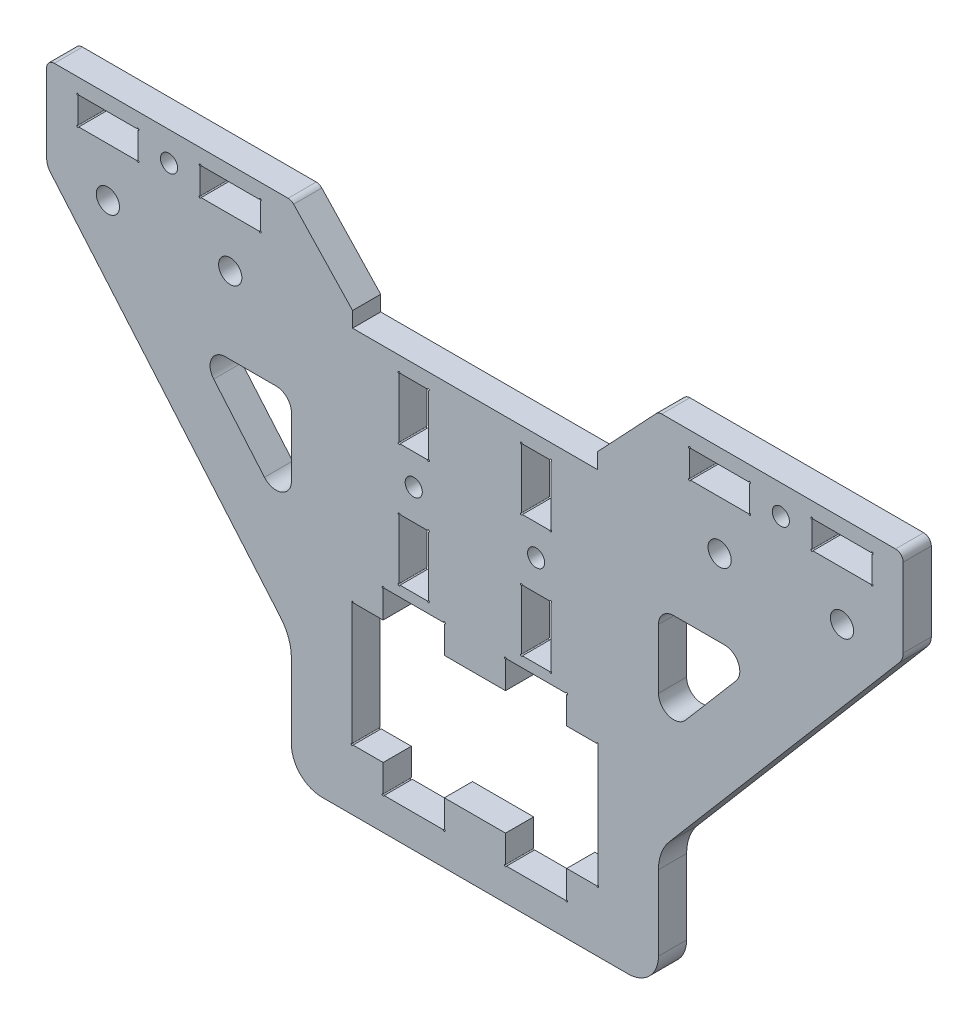
SolidWorks part; units mm, degrees
ref_plane "Front Plane" through (0, 0, 0) normal (0, 0, 1) x (1, 0, 0)
ref_plane "Top Plane" through (0, 0, 0) normal (0, 1, 0) x (1, 0, 0)
ref_plane "Right Plane" through (0, 0, 0) normal (1, 0, 0) x (0, 0, -1)
sketch "Sketch1" plane through (0, 0, 0) normal (0, 0, 1) x (1, 0, 0)
  line L0 (0, 0) -> (-101.6, 0) construction
  line L1 (-25.4, 2.4354) -> (-76.2, 2.4354)
  line L2 (0, 0) -> (12.7, 0) construction
  line L3 (12.7, 0) -> (12.7, 41.9354) construction
  line L4 (12.7, 0) -> (25.4, 0) construction
  line L5 (-101.6, 0) -> (-114.3, 0) construction
  line L6 (-114.3, 0) -> (-127, 0) construction
  line L7 (-114.3, 0) -> (-114.3, 41.9354) construction
  line L8 (49.2125, 41.9354) -> (-23.8125, 41.9354) construction
  line L9 (-150.8125, 41.9354) -> (-77.7875, 41.9354) construction
  line L10 (6.25, 10.1854) -> (-6.25, 10.1854)
  line L11 (19.15, 15.9274) -> (31.65, 15.9274)
  line L12 (19.15, 15.9274) -> (19.15, 10.1854)
  line L13 (33.7058, 10.1854) -> (-8.3058, 10.1854) construction
  line L14 (33.7058, 10.1854) -> (33.7058, 15.9274) construction
  line L15 (33.7058, 15.9274) -> (-8.3058, 15.9274) construction
  line L16 (-8.3058, 10.1854) -> (-8.3058, 15.9274) construction
  line L17 (12.7, 15.9274) -> (12.7, 10.1854) construction
  line L18 (33.7058, 13.0564) -> (-8.3058, 13.0564) construction
  line L19 (19.15, 10.1854) -> (31.65, 10.1854)
  line L20 (31.65, 15.9274) -> (31.65, 10.1854)
  line L21 (19.15, 15.9274) -> (31.65, 10.1854) construction
  line L22 (19.15, 10.1854) -> (31.65, 15.9274) construction
  line L23 (-6.25, 15.9274) -> (-6.25, 10.1854)
  line L24 (6.25, 15.9274) -> (-6.25, 15.9274)
  line L25 (6.25, 15.9274) -> (6.25, 10.1854)
  line L26 (38.1, 19.1024) -> (-12.7, 19.1024)
  line L27 (-25.4, 2.4354) -> (-25.4, 5.6104)
  line L28 (-50.8, 41.9354) -> (-50.8, -59.6646) construction
  line L29 (38.1, 19.1024) -> (38.1, 0)
  line L30 (-25.4, -72.3646) -> (-76.2, -72.3646) construction
  line L31 (-25.4, -72.3646) -> (-25.4, -46.9646) construction
  line L32 (-25.4, -46.9646) -> (-76.2, -46.9646) construction
  line L33 (-76.2, -72.3646) -> (-76.2, -46.9646) construction
  line L34 (-25.4, -72.3646) -> (-76.2, -46.9646) construction
  line L35 (-25.4, -46.9646) -> (-76.2, -72.3646) construction
  line L36 (-25.4, 5.6104) -> (-12.7, 19.1024)
  line L37 (-25.3, -72.4646) -> (-76.3, -72.4646)
  line L38 (-25.3, -72.4646) -> (-25.3, -46.8646)
  line L39 (-25.3, -46.8646) -> (-76.3, -46.8646)
  line L40 (-76.3, -72.4646) -> (-76.3, -46.8646)
  line L41 (-25.3, -72.4646) -> (-76.3, -46.8646) construction
  line L42 (-25.3, -46.8646) -> (-76.3, -72.4646) construction
  line L43 (-12.7, -59.6646) -> (38.1, 0)
  line L44 (-12.7, -85.0646) -> (-88.9, -85.0646)
  line L45 (-12.7, -85.0646) -> (-12.7, -59.6646)
  line L47 (-12.7, -40.0743) -> (7.8828, -15.8997)
  line L48 (-12.7, -85.0646) -> (-88.9, -34.2646) construction
  line L49 (-12.7, -34.2646) -> (-88.9, -85.0646) construction
  line L56 (-12.7, -59.6646) -> (-12.7, -40.0743) construction
  line L57 (-12.7, -40.0743) -> (-12.7, -15.8997)
  line L58 (-12.7, -15.8997) -> (7.8828, -15.8997)
  line L67 (-88.9, -59.6646) -> (-88.9, -40.0743) construction
  line L70 (-88.9, -34.2646) -> (-12.7, -85.0646) construction
  line L71 (-120.75, 10.1854) -> (-133.25, 15.9274) construction
  line L72 (-120.75, 15.9274) -> (-133.25, 10.1854) construction
  line L73 (-135.3058, 13.0564) -> (-93.2942, 13.0564) construction
  line L74 (-114.3, 15.9274) -> (-114.3, 10.1854) construction
  line L75 (-93.2942, 10.1854) -> (-93.2942, 15.9274) construction
  line L76 (-135.3058, 15.9274) -> (-93.2942, 15.9274) construction
  line L77 (-135.3058, 10.1854) -> (-135.3058, 15.9274) construction
  line L78 (-135.3058, 10.1854) -> (-93.2942, 10.1854) construction
  line L79 (-114.3, 0) -> (-127, 0) construction
  line L80 (-114.3, 0) -> (-114.3, 41.9354) construction
  line L81 (-101.6, 0) -> (-114.3, 0) construction
  line L86 (-88.9, -15.8997) -> (-109.4828, -15.8997)
  line L87 (-88.9, -40.0743) -> (-88.9, -15.8997)
  line L92 (-88.9, -40.0743) -> (-109.4828, -15.8997)
  line L93 (-88.9, -59.6646) -> (-139.7, 0)
  line L94 (-76.2, 5.6104) -> (-88.9, 19.1024)
  line L95 (-139.7, 19.1024) -> (-139.7, 0)
  line L96 (-76.2, 2.4354) -> (-76.2, 5.6104)
  line L97 (-139.7, 19.1024) -> (-88.9, 19.1024)
  line L98 (-107.85, 15.9274) -> (-107.85, 10.1854)
  line L99 (-107.85, 15.9274) -> (-95.35, 15.9274)
  line L100 (-95.35, 15.9274) -> (-95.35, 10.1854)
  line L101 (-133.25, 15.9274) -> (-133.25, 10.1854)
  line L102 (-120.75, 10.1854) -> (-133.25, 10.1854)
  line L103 (-120.75, 15.9274) -> (-120.75, 10.1854)
  line L104 (-120.75, 15.9274) -> (-133.25, 15.9274)
  line L105 (-107.85, 10.1854) -> (-95.35, 10.1854)
  line L106 (-88.9, -85.0646) -> (-88.9, -59.6646)
  circle A0 centre (0, 0) radius 2.413
  circle A1 centre (-101.6, 0) radius 2.413
  circle A2 centre (25.4, 0) radius 2.413
  circle A3 centre (-127, 0) radius 2.413
  circle A4 centre (-50.8, 41.9354) radius 34.925 construction
  circle A5 centre (12.7, 13.0564) radius 1.778
  circle A24 centre (-114.3, 13.0564) radius 1.778
  circle A25 centre (-127, 0) radius 2.413
  circle A26 centre (-101.6, 0) radius 2.413
  ellipse E0 centre (-50.8, 41.9354) end of major axis (-50.8, 76.8604) minor radius 26.9875 construction
  point P5 (-114.3, 19.1024)
  point P17 (12.7, 41.9354)
  point P22 (12.7, 13.0564)
  point P25 (12.7, 13.1064)
  point P28 (12.7, 10.1854)
  point P32 (25.4, 13.0564)
  point P42 (12.7, 19.1024)
  point P48 (-50.8, 0.4064)
  point P51 (-50.8, -59.6646)
  point P68 (-50.8, -10.7061)
  point P100 (-50.8, -20.2311)
  point P126 (-50.8, -22.225)
  point P163 (-50.8, 2.4354)
  point P164 (-127, 13.0564)
  point P165 (-114.3, 13.1064)
  dimension "D1" = 4.826
  dimension "D2" = 4.826
  dimension "D4" = 4.826
  dimension "D5" = 4.826
  dimension "D9" = 69.85
  dimension "D16" = 3.556
  dimension "D3" = 12.7
  dimension "D6" = 12.7
  dimension "D7" = 127
  dimension "D8" = 73.025
  dimension "D10" = 31.75
  dimension "D11" = 10.1854
  dimension "D12" = 12.5
  dimension "D13" = 5.742
  dimension "D14" = 42.0116
  dimension "D15" = 12.7
  dimension "D17" = 50.8
  dimension "D18" = 4.575
  dimension "D19" = 3.175
  dimension "D20" = 101.6
  dimension "D21" = 50.8
  dimension "D22" = 25.4
  dimension "D23" = 25.4
  dimension "D24" = 51
  dimension "D25" = 25.6
  dimension "D26" = 3.175
  dimension "D28" = 50.8
  dimension "D29" = 25.4
  dimension "D37" = 12.7
  dimension "D38" = 31.75
extrude "Boss-Extrude1" add sketch "Sketch1" along normal blind 5.842
fillet "Fillet1" radius 6.35 2 edges at (-12.7, -85.0646, 2.921) (-88.9, -85.0646, 2.921)
fillet "Fillet2" radius 3.175 6 edges at (7.8828, -15.8997, 2.921) (-12.7, -40.0743, 2.921) (-12.7, -15.8997, 2.921) (-88.9, -15.8997, 2.921) (-88.9, -40.0743, 2.921) (-109.4828, -15.8997, 2.921)
fillet "Fillet3" radius 3.175 2 edges at (-139.7, 0, 2.921) (38.1, 0, 2.921)
fillet "Fillet4" radius 1.5875 4 edges at (38.1, 19.1024, 2.921) (-12.7, 19.1024, 2.921) (-88.9, 19.1024, 2.921) (-139.7, 19.1024, 2.921)
fillet "Fillet5" radius 9.525 2 edges at (-88.9, -59.6646, 2.921) (-12.7, -59.6646, 2.921)
sketch "Sketch2" plane through (0, 0, 5.842) normal (0, 0, 1) x (1, 0, 0)
  line L0 (-50.8, 2.4354) -> (-50.8, -46.8646) construction
  line L1 (-25.4, 2.4354) -> (-76.2, 2.4354) construction
  line L2 (-25.3, -46.8646) -> (-76.3, -46.8646) construction
  line L3 (-38.1, -19.7896) -> (-63.5, -19.7896) construction
  line L4 (-38.1, -32.4896) -> (-38.1, -7.0896) construction
  line L5 (-35.052, -26.1396) -> (-41.148, -38.8396) construction
  line L6 (-35.052, -0.7396) -> (-41.148, -0.7396)
  line L7 (-35.052, -0.7396) -> (-35.052, -13.4396)
  line L8 (-35.052, -13.4396) -> (-41.148, -13.4396)
  line L9 (-41.148, -0.7396) -> (-41.148, -13.4396)
  line L10 (-35.052, -0.7396) -> (-41.148, -13.4396) construction
  line L11 (-35.052, -13.4396) -> (-41.148, -0.7396) construction
  line L12 (-35.052, -38.8396) -> (-41.148, -26.1396) construction
  line L13 (-41.148, -38.8396) -> (-41.148, -26.1396)
  line L14 (-35.052, -26.1396) -> (-41.148, -26.1396)
  line L15 (-35.052, -38.8396) -> (-35.052, -26.1396)
  line L16 (-35.052, -38.8396) -> (-41.148, -38.8396)
  line L17 (-66.548, -38.8396) -> (-60.452, -26.1396) construction
  line L18 (-66.548, -13.4396) -> (-60.452, -0.7396) construction
  line L19 (-66.548, -0.7396) -> (-60.452, -13.4396) construction
  line L20 (-66.548, -26.1396) -> (-60.452, -38.8396) construction
  line L21 (-63.5, -32.4896) -> (-63.5, -7.0896) construction
  line L22 (-66.548, -38.8396) -> (-60.452, -38.8396)
  line L23 (-66.548, -38.8396) -> (-66.548, -26.1396)
  line L24 (-66.548, -26.1396) -> (-60.452, -26.1396)
  line L25 (-60.452, -38.8396) -> (-60.452, -26.1396)
  line L26 (-60.452, -0.7396) -> (-60.452, -13.4396)
  line L27 (-66.548, -13.4396) -> (-60.452, -13.4396)
  line L28 (-66.548, -0.7396) -> (-66.548, -13.4396)
  line L29 (-66.548, -0.7396) -> (-60.452, -0.7396)
  circle A0 centre (-38.1, -19.7896) radius 1.778
  circle A1 centre (-63.5, -19.7896) radius 1.778
  point P9 (-50.8, -19.7896)
  point P12 (-38.1, -19.7896)
  dimension "D6" = 3.556
  dimension "D1" = 25.4
  dimension "D2" = 25.4
  dimension "D3" = 22.225
  dimension "D4" = 6.096
  dimension "D5" = 12.7
extrude "Cut-Extrude1" cut sketch "Sketch2" against normal through all
sketch "Sketch3" plane through (0, 0, 5.842) normal (0, 0, 1) x (1, 0, 0)
  line L1 (-50.8, 2.4354) -> (-50.8, -46.8646) construction
  line L2 (-25.4, 2.4354) -> (-76.2, 2.4354) construction
  line L3 (-25.3, -46.8646) -> (-76.3, -46.8646) construction
  circle A0 centre (-35.052, -26.1396) radius 0.1984
  circle A1 centre (-41.148, -26.1396) radius 0.1984
  circle A2 centre (-35.052, -38.8396) radius 0.1984
  circle A3 centre (-41.148, -38.8396) radius 0.1984
  circle A4 centre (-35.052, -0.7396) radius 0.1984
  circle A5 centre (-35.052, -13.4396) radius 0.1984
  circle A6 centre (-41.148, -13.4396) radius 0.1984
  circle A7 centre (-41.148, -0.7396) radius 0.1984
  circle A24 centre (-60.452, -0.7396) radius 0.1984
  circle A25 centre (-60.452, -13.4396) radius 0.1984
  circle A26 centre (-66.548, -13.4396) radius 0.1984
  circle A27 centre (-66.548, -0.7396) radius 0.1984
  circle A28 centre (-60.452, -38.8396) radius 0.1984
  circle A29 centre (-66.548, -38.8396) radius 0.1984
  circle A30 centre (-60.452, -26.1396) radius 0.1984
  circle A31 centre (-66.548, -26.1396) radius 0.1984
  dimension "D9" = 0.3969
  dimension "D10" = 0.3969
  dimension "D11" = 0.3969
  dimension "D12" = 0.3969
  dimension "D13" = 0.3969
  dimension "D14" = 0.3969
  dimension "D15" = 0.3969
  dimension "D16" = 0.3969
extrude "Cut-Extrude2" cut sketch "Sketch3" against normal through all
sketch "Sketch5" plane through (0, 0, 5.842) normal (0, 0, 1) x (1, 0, 0)
  line L0 (19.15, 15.9274) -> (19.15, 10.1854) construction
  line L1 (19.15, 15.9274) -> (31.65, 15.9274) construction
  line L2 (-50.8, 2.4354) -> (-50.8, -46.8646) construction
  line L3 (-25.4, 2.4354) -> (-76.2, 2.4354) construction
  line L4 (-25.3, -46.8646) -> (-76.3, -46.8646) construction
  circle A0 centre (31.65, 15.9274) radius 0.1984
  circle A1 centre (31.65, 10.1854) radius 0.1984
  circle A2 centre (19.15, 10.1854) radius 0.1984
  circle A3 centre (19.15, 15.9274) radius 0.1984
  circle A4 centre (6.25, 15.9274) radius 0.1984
  circle A5 centre (6.25, 10.1854) radius 0.1984
  circle A6 centre (-6.25, 15.9274) radius 0.1984
  circle A7 centre (-6.25, 10.1854) radius 0.1984
  circle A8 centre (-95.35, 10.1854) radius 0.1984
  circle A9 centre (-95.35, 15.9274) radius 0.1984
  circle A10 centre (-107.85, 10.1854) radius 0.1984
  circle A11 centre (-107.85, 15.9274) radius 0.1984
  circle A12 centre (-120.75, 15.9274) radius 0.1984
  circle A13 centre (-120.75, 10.1854) radius 0.1984
  circle A14 centre (-133.25, 10.1854) radius 0.1984
  circle A15 centre (-133.25, 15.9274) radius 0.1984
  circle A16 centre (-25.3, -46.8646) radius 0.1984
  circle A17 centre (-25.3, -72.4646) radius 0.1984
  circle A18 centre (-76.3, -72.4646) radius 0.1984
  circle A19 centre (-76.3, -46.8646) radius 0.1984
  dimension "D1" = 0.3969
  dimension "D2" = 0.3969
  dimension "D3" = 0.3969
  dimension "D4" = 0.3969
  dimension "D5" = 0.3969
  dimension "D6" = 0.3969
  dimension "D7" = 0.3969
  dimension "D8" = 0.3969
  dimension "D9" = 0.3969
  dimension "D10" = 0.3969
  dimension "D11" = 0.3969
  dimension "D12" = 0.3969
extrude "Cut-Extrude3" cut sketch "Sketch5" against normal through all
sketch "Sketch6" [suppressed] plane through (0, 0, 5.842) normal (0, 0, 1) x (1, 0, 0)
  line L0 (-76.3, -72.2662) -> (-76.3, -47.063) construction
  line L1 (-76.3, -59.6646) -> (-25.3, -59.6646) construction
  line L2 (-25.3, -72.2662) -> (-25.3, -47.063) construction
  line L3 (-82.142, -43.7896) -> (-76.3, -43.7896)
  line L4 (-82.142, -43.7896) -> (-82.142, -56.4896)
  line L5 (-82.142, -56.4896) -> (-76.3, -56.4896)
  line L6 (-76.3, -43.7896) -> (-76.3, -56.4896)
  line L7 (-82.142, -43.7896) -> (-76.3, -56.4896) construction
  line L8 (-82.142, -56.4896) -> (-76.3, -43.7896) construction
  line L9 (-79.221, -50.1396) -> (-79.221, -75.5396) construction
  line L10 (-44.45, -46.8646) -> (-31.75, -41.0226) construction
  line L11 (-44.45, -41.0226) -> (-31.75, -46.8646) construction
  line L12 (-76.3, -62.8396) -> (-82.142, -62.8396) construction
  line L13 (-82.142, -69.1896) -> (-76.3, -81.8896) construction
  line L14 (-82.142, -81.8896) -> (-76.3, -69.1896) construction
  line L15 (-76.3, -81.8896) -> (-76.3, -69.1896)
  line L16 (-82.142, -69.1896) -> (-76.3, -69.1896)
  line L17 (-82.142, -81.8896) -> (-82.142, -69.1896)
  line L18 (-82.142, -81.8896) -> (-76.3, -81.8896)
  line L19 (-19.05, -85.0646) -> (-82.55, -85.0646) construction
  line L20 (-50.8, -85.0646) -> (-50.8, 2.4354) construction
  line L21 (-25.4, 2.4354) -> (-76.2, 2.4354) construction
  line L22 (-79.221, -50.1396) -> (-79.221, 8.8198) construction
  line L23 (-76.2, 5.6104) -> (-88.4299, 18.603) construction
  line L24 (-38.1, -19.7896) -> (-63.5, -19.7896) construction
  line L25 (-60.452, -7.0896) -> (-79.221, -7.0896) construction
  line L26 (-60.452, -13.2412) -> (-60.452, -0.938) construction
  line L27 (-60.452, -32.4896) -> (-79.221, -32.4896) construction
  line L28 (-60.452, -38.6412) -> (-60.452, -26.338) construction
  line L29 (-76.3, -26.1396) -> (-82.142, -38.8396) construction
  line L30 (-76.3, -0.7396) -> (-82.142, -0.7396)
  line L31 (-76.3, -0.7396) -> (-76.3, -13.4396)
  line L32 (-76.3, -13.4396) -> (-82.142, -13.4396)
  line L33 (-82.142, -0.7396) -> (-82.142, -13.4396)
  line L34 (-76.3, -0.7396) -> (-82.142, -13.4396) construction
  line L35 (-76.3, -13.4396) -> (-82.142, -0.7396) construction
  line L36 (-76.3, -38.8396) -> (-82.142, -26.1396) construction
  line L37 (-82.142, -38.8396) -> (-82.142, -26.1396)
  line L38 (-76.3, -26.1396) -> (-82.142, -26.1396)
  line L39 (-25.4984, -46.8646) -> (-76.1016, -46.8646) construction
  line L40 (-57.15, -41.0226) -> (-69.85, -41.0226)
  line L41 (-57.15, -41.0226) -> (-57.15, -46.8646)
  line L42 (-57.15, -46.8646) -> (-69.85, -46.8646)
  line L43 (-69.85, -41.0226) -> (-69.85, -46.8646)
  line L44 (-57.15, -41.0226) -> (-69.85, -46.8646) construction
  line L45 (-57.15, -46.8646) -> (-69.85, -41.0226) construction
  line L46 (-31.75, -41.0226) -> (-31.75, -46.8646)
  line L47 (-44.45, -46.8646) -> (-31.75, -46.8646)
  line L48 (-44.45, -41.0226) -> (-44.45, -46.8646)
  line L49 (-44.45, -41.0226) -> (-31.75, -41.0226)
  line L50 (-57.15, -72.4646) -> (-69.85, -78.3066) construction
  line L51 (-57.15, -78.3066) -> (-69.85, -72.4646) construction
  line L52 (-44.45, -78.3066) -> (-31.75, -72.4646) construction
  line L53 (-44.45, -72.4646) -> (-31.75, -78.3066) construction
  line L54 (-44.45, -78.3066) -> (-31.75, -78.3066)
  line L55 (-44.45, -78.3066) -> (-44.45, -72.4646)
  line L56 (-44.45, -72.4646) -> (-31.75, -72.4646)
  line L57 (-31.75, -78.3066) -> (-31.75, -72.4646)
  line L58 (-69.85, -78.3066) -> (-69.85, -72.4646)
  line L59 (-57.15, -72.4646) -> (-69.85, -72.4646)
  line L60 (-57.15, -78.3066) -> (-57.15, -72.4646)
  line L61 (-57.15, -78.3066) -> (-69.85, -78.3066)
  line L62 (-76.3, -38.8396) -> (-76.3, -26.1396)
  line L63 (-76.3, -38.8396) -> (-82.142, -38.8396)
  line L64 (-25.3, -38.8396) -> (-19.458, -26.1396) construction
  line L65 (-25.3, -13.4396) -> (-19.458, -0.7396) construction
  line L66 (-25.3, -0.7396) -> (-19.458, -13.4396) construction
  line L67 (-25.3, -26.1396) -> (-19.458, -38.8396) construction
  line L68 (-19.458, -81.8896) -> (-25.3, -69.1896) construction
  line L69 (-19.458, -69.1896) -> (-25.3, -81.8896) construction
  line L70 (-25.3, -62.8396) -> (-19.458, -62.8396) construction
  line L71 (-22.379, -50.1396) -> (-22.379, -75.5396) construction
  line L72 (-19.458, -56.4896) -> (-25.3, -43.7896) construction
  line L73 (-19.458, -43.7896) -> (-25.3, -56.4896) construction
  line L74 (-25.3, -38.8396) -> (-19.458, -38.8396)
  line L75 (-25.3, -38.8396) -> (-25.3, -26.1396)
  line L76 (-25.3, -26.1396) -> (-19.458, -26.1396)
  line L77 (-19.458, -38.8396) -> (-19.458, -26.1396)
  line L78 (-19.458, -0.7396) -> (-19.458, -13.4396)
  line L79 (-25.3, -13.4396) -> (-19.458, -13.4396)
  line L80 (-25.3, -0.7396) -> (-25.3, -13.4396)
  line L81 (-25.3, -0.7396) -> (-19.458, -0.7396)
  line L82 (-19.458, -81.8896) -> (-25.3, -81.8896)
  line L83 (-19.458, -81.8896) -> (-19.458, -69.1896)
  line L84 (-19.458, -69.1896) -> (-25.3, -69.1896)
  line L85 (-25.3, -81.8896) -> (-25.3, -69.1896)
  line L86 (-25.3, -43.7896) -> (-25.3, -56.4896)
  line L87 (-19.458, -56.4896) -> (-25.3, -56.4896)
  line L88 (-19.458, -43.7896) -> (-19.458, -56.4896)
  line L89 (-19.458, -43.7896) -> (-25.3, -43.7896)
  circle A0 centre (-79.221, -62.8396) radius 1.778
  circle A1 centre (-79.221, -18.6436) radius 1.778
  circle A2 centre (-50.8, -43.9436) radius 1.778
  circle A3 centre (-50.8, -75.3856) radius 1.778
  circle A4 centre (-22.379, -18.6436) radius 1.778
  circle A5 centre (-22.379, -62.8396) radius 1.778
  point P0 (-79.221, -50.1396)
  point P12 (-79.221, -62.8396)
  point P44 (-63.5, -43.9436)
  point P61 (-38.1, -43.9436)
  point P72 (-38.1, -75.3856)
  point P73 (-63.5, -75.3856)
  dimension "D4" = 3.556
  dimension "D10" = 3.556
  dimension "D6" = 3.556
  dimension "D1" = 5.842
  dimension "D2" = 12.7
  dimension "D3" = 25.4
  dimension "D5" = 3.175
  dimension "D7" = 5.842
  dimension "D8" = 5.842
  dimension "D9" = 12.7
  dimension "D11" = 12.7
extrude "Cut-Extrude4" [suppressed] cut sketch "Sketch6" against normal through all
sketch "Sketch7" [suppressed] plane through (0, 0, 5.842) normal (0, 0, 1) x (1, 0, 0)
  line L0 (-63.5, -85.0646) -> (-63.5, -91.4146)
  line L1 (-19.05, -85.0646) -> (-82.55, -85.0646) construction
  line L2 (-88.9, -78.7146) -> (-88.9, -63.1702) construction
  line L3 (-63.5, -110.4646) -> (-76.2, -110.4646)
  line L4 (-63.5, -85.0646) -> (-82.55, -85.0646)
  line L5 (-76.2, -110.4646) -> (-88.4115, -81.1569)
  line L6 (-50.8, -46.8646) -> (-50.8, -72.4646) construction
  line L7 (-25.4984, -46.8646) -> (-76.1016, -46.8646) construction
  line L8 (-25.4984, -72.4646) -> (-76.1016, -72.4646) construction
  line L9 (-25.4, -110.4646) -> (-13.1885, -81.1569)
  line L10 (-38.1, -85.0646) -> (-19.05, -85.0646)
  line L11 (-38.1, -110.4646) -> (-25.4, -110.4646)
  line L12 (-38.1, -85.0646) -> (-38.1, -91.4146)
  line L13 (-63.5, -97.7646) -> (-38.1, -97.7646) construction
  line L14 (-63.5, -104.1146) -> (-63.5, -110.4646)
  line L15 (-69.342, -104.1146) -> (-63.5, -104.1146)
  line L16 (-69.342, -104.1146) -> (-69.342, -91.4146)
  line L17 (-69.342, -91.4146) -> (-63.5, -91.4146)
  line L18 (-32.258, -91.4146) -> (-38.1, -104.1146) construction
  line L19 (-69.342, -104.1146) -> (-63.5, -91.4146) construction
  line L20 (-69.342, -91.4146) -> (-63.5, -104.1146) construction
  line L21 (-32.258, -104.1146) -> (-38.1, -91.4146) construction
  line L22 (-32.258, -91.4146) -> (-38.1, -91.4146)
  line L23 (-32.258, -104.1146) -> (-32.258, -91.4146)
  line L24 (-32.258, -104.1146) -> (-38.1, -104.1146)
  line L25 (-38.1, -104.1146) -> (-38.1, -110.4646)
  arc A0 (-88.9, -78.7146) -> (-82.55, -85.0646) centre (-82.55, -78.7146) ccw construction
  arc A1 (-88.4115, -81.1569) -> (-82.55, -85.0646) centre (-82.55, -78.7146) ccw
  arc A2 (-13.1885, -81.1569) -> (-19.05, -85.0646) centre (-19.05, -78.7146) cw
  point P23 (-66.421, -97.7646)
  point P32 (-35.179, -97.7646)
  dimension "D1" = 25.4
  dimension "D2" = 25.4
  dimension "D3" = 12.7
  dimension "D4" = 5.842
  dimension "D5" = 12.7
extrude "Boss-Extrude2" [suppressed] add sketch "Sketch7" against normal up to surface (5.842 mm away)
fillet "Fillet6" [suppressed] radius 3.175
fillet "Fillet7" [suppressed] radius 1.5875
sketch "Sketch8" [suppressed] plane through (0, 0, 5.842) normal (0, 0, 1) x (1, 0, 0)
  line L0 (-76.3, -46.6662) -> (-76.3, -43.7896) construction
  line L1 (-76.3, -43.7896) -> (-82.142, -43.7896) construction
  line L3 (-50.8, -72.4646) -> (-50.8, -46.8646) construction
  line L4 (-44.45, -72.4646) -> (-57.15, -72.4646) construction
  line L5 (-44.45, -46.8646) -> (-57.15, -46.8646) construction
  circle A0 centre (-82.142, 0.4064) radius 0.1984
  circle A1 centre (-76.3, 0.4064) radius 0.1984
  circle A2 centre (-76.3, -12.2936) radius 0.1984
  circle A3 centre (-82.142, -12.2936) radius 0.1984
  circle A4 centre (-82.142, -24.9936) radius 0.1984
  circle A5 centre (-76.3, -24.9936) radius 0.1984
  circle A6 centre (-76.3, -37.6936) radius 0.1984
  circle A7 centre (-82.142, -37.6936) radius 0.1984
  circle A8 centre (-69.85, -41.0226) radius 0.1984
  circle A9 centre (-57.15, -41.0226) radius 0.1984
  circle A10 centre (-82.142, -43.7896) radius 0.1984
  circle A11 centre (-76.3, -43.7896) radius 0.1984
  circle A12 centre (-82.142, -56.4896) radius 0.1984
  circle A13 centre (-82.142, -69.1896) radius 0.1984
  circle A14 centre (-82.142, -81.8896) radius 0.1984
  circle A15 centre (-76.3, -81.8896) radius 0.1984
  circle A16 centre (-69.85, -78.3066) radius 0.1984
  circle A17 centre (-57.15, -78.3066) radius 0.1984
  circle A18 centre (-69.342, -91.4146) radius 0.1984
  circle A19 centre (-69.342, -104.1146) radius 0.1984
  circle A20 centre (-32.258, -104.1146) radius 0.1984
  circle A21 centre (-32.258, -91.4146) radius 0.1984
  circle A22 centre (-44.45, -78.3066) radius 0.1984
  circle A23 centre (-31.75, -78.3066) radius 0.1984
  circle A24 centre (-25.3, -81.8896) radius 0.1984
  circle A25 centre (-19.458, -81.8896) radius 0.1984
  circle A26 centre (-19.458, -69.1896) radius 0.1984
  circle A27 centre (-19.458, -56.4896) radius 0.1984
  circle A28 centre (-25.3, -43.7896) radius 0.1984
  circle A29 centre (-19.458, -43.7896) radius 0.1984
  circle A30 centre (-44.45, -41.0226) radius 0.1984
  circle A31 centre (-31.75, -41.0226) radius 0.1984
  circle A32 centre (-19.458, -37.6936) radius 0.1984
  circle A33 centre (-25.3, -37.6936) radius 0.1984
  circle A34 centre (-25.3, -24.9936) radius 0.1984
  circle A35 centre (-19.458, -24.9936) radius 0.1984
  circle A36 centre (-19.458, -12.2936) radius 0.1984
  circle A37 centre (-25.3, -12.2936) radius 0.1984
  circle A38 centre (-25.3, 0.4064) radius 0.1984
  circle A39 centre (-19.458, 0.4064) radius 0.1984
  dimension "D1" = 0.3969
  dimension "D2" = 0.3969
  dimension "D3" = 0.3969
  dimension "D4" = 0.3969
  dimension "D5" = 0.3969
  dimension "D6" = 0.3969
  dimension "D7" = 0.3969
  dimension "D8" = 0.3969
  dimension "D9" = 0.3969
  dimension "D10" = 0.3969
  dimension "D11" = 0.3969
  dimension "D12" = 0.3969
  dimension "D13" = 0.3969
  dimension "D14" = 0.3969
  dimension "D15" = 0.3969
  dimension "D16" = 0.3969
  dimension "D17" = 0.3969
  dimension "D18" = 0.3969
  dimension "D19" = 0.3969
  dimension "D20" = 0.3969
extrude "Cut-Extrude5" [suppressed] cut sketch "Sketch8" against normal through all
sketch "Sketch9" plane through (0, 0, 5.842) normal (0, 0, 1) x (1, 0, 0)
  line L0 (-50.8, -46.8646) -> (-50.8, -72.4646) construction
  line L1 (-25.4984, -46.8646) -> (-76.1016, -46.8646) construction
  line L2 (-25.4984, -72.4646) -> (-76.1016, -72.4646) construction
  line L3 (-25.3, -59.6646) -> (-76.3, -59.6646) construction
  line L4 (-25.3, -72.2662) -> (-25.3, -47.063) construction
  line L5 (-76.3, -72.2662) -> (-76.3, -47.063) construction
  line L6 (-31.75, -46.8646) -> (-44.45, -41.0226) construction
  line L7 (-69.85, -41.0226) -> (-57.15, -41.0226)
  line L8 (-69.85, -41.0226) -> (-69.85, -46.8646)
  line L9 (-69.85, -46.8646) -> (-57.15, -46.8646)
  line L10 (-57.15, -41.0226) -> (-57.15, -46.8646)
  line L11 (-69.85, -41.0226) -> (-57.15, -46.8646) construction
  line L12 (-69.85, -46.8646) -> (-57.15, -41.0226) construction
  line L13 (-31.75, -41.0226) -> (-44.45, -46.8646) construction
  line L14 (-44.45, -41.0226) -> (-44.45, -46.8646)
  line L15 (-31.75, -46.8646) -> (-44.45, -46.8646)
  line L16 (-31.75, -41.0226) -> (-31.75, -46.8646)
  line L17 (-31.75, -41.0226) -> (-44.45, -41.0226)
  line L18 (-31.75, -78.3066) -> (-44.45, -72.4646) construction
  line L19 (-69.85, -72.4646) -> (-57.15, -78.3066) construction
  line L20 (-69.85, -78.3066) -> (-57.15, -72.4646) construction
  line L21 (-31.75, -72.4646) -> (-44.45, -78.3066) construction
  line L22 (-31.75, -78.3066) -> (-44.45, -78.3066)
  line L23 (-31.75, -78.3066) -> (-31.75, -72.4646)
  line L24 (-31.75, -72.4646) -> (-44.45, -72.4646)
  line L25 (-44.45, -78.3066) -> (-44.45, -72.4646)
  line L26 (-57.15, -78.3066) -> (-57.15, -72.4646)
  line L27 (-69.85, -72.4646) -> (-57.15, -72.4646)
  line L28 (-69.85, -78.3066) -> (-69.85, -72.4646)
  line L29 (-69.85, -78.3066) -> (-57.15, -78.3066)
  line L30 (-19.458, -53.3146) -> (-25.3, -66.0146) construction
  line L31 (-82.142, -66.0146) -> (-76.3, -66.0146)
  line L32 (-82.142, -66.0146) -> (-82.142, -53.3146)
  line L33 (-82.142, -53.3146) -> (-76.3, -53.3146)
  line L34 (-76.3, -66.0146) -> (-76.3, -53.3146)
  line L35 (-82.142, -66.0146) -> (-76.3, -53.3146) construction
  line L36 (-82.142, -53.3146) -> (-76.3, -66.0146) construction
  line L37 (-19.458, -66.0146) -> (-25.3, -53.3146) construction
  line L38 (-25.3, -66.0146) -> (-25.3, -53.3146)
  line L39 (-19.458, -53.3146) -> (-25.3, -53.3146)
  line L40 (-19.458, -66.0146) -> (-19.458, -53.3146)
  line L41 (-19.458, -66.0146) -> (-25.3, -66.0146)
  line L42 (-22.379, -59.6646) -> (-22.379, 8.8198) construction
  line L43 (-25.4, 5.6104) -> (-13.1701, 18.603) construction
  line L44 (-79.221, -59.6646) -> (-79.221, 8.8198) construction
  line L45 (-76.2, 5.6104) -> (-88.4299, 18.603) construction
  line L46 (-19.458, -27.9146) -> (-25.3, -27.9146)
  line L47 (-25.3, -40.6146) -> (-25.3, -27.9146)
  line L48 (-19.458, -40.6146) -> (-25.3, -40.6146)
  line L49 (-19.458, -40.6146) -> (-19.458, -27.9146)
  line L50 (-19.458, -2.5146) -> (-25.3, -2.5146)
  line L51 (-25.3, -15.2146) -> (-25.3, -2.5146)
  line L52 (-19.458, -15.2146) -> (-25.3, -15.2146)
  line L53 (-19.458, -15.2146) -> (-19.458, -2.5146)
  line L54 (-82.142, -15.2146) -> (-82.142, -2.5146)
  line L55 (-82.142, -15.2146) -> (-76.3, -15.2146)
  line L56 (-76.3, -15.2146) -> (-76.3, -2.5146)
  line L57 (-82.142, -2.5146) -> (-76.3, -2.5146)
  line L58 (-82.142, -40.6146) -> (-82.142, -27.9146)
  line L59 (-82.142, -40.6146) -> (-76.3, -40.6146)
  line L60 (-76.3, -40.6146) -> (-76.3, -27.9146)
  line L61 (-82.142, -27.9146) -> (-76.3, -27.9146)
  point P12 (-63.5, -43.9436)
  point P21 (-38.1, -43.9436)
  point P30 (-38.1, -75.3856)
  point P31 (-63.5, -75.3856)
  point P32 (-79.221, -59.6646)
  point P41 (-22.379, -59.6646)
  dimension "D1" = 5.842
  dimension "D2" = 12.7
  dimension "D3" = 12.7
  dimension "D4" = 5.842
  dimension "D5" = 12.7
  dimension "D6" = 3
extrude "Cut-Extrude6" cut sketch "Sketch9" against normal through all
sketch "Sketch10" plane through (0, 0, 5.842) normal (0, 0, 1) x (1, 0, 0)
  line L0 (-50.8, -46.8646) -> (-50.8, -72.4646) construction
  line L1 (-44.45, -46.8646) -> (-57.15, -46.8646) construction
  line L2 (-44.45, -72.4646) -> (-57.15, -72.4646) construction
  circle A0 centre (-44.45, -41.0226) radius 0.1984
  circle A1 centre (-31.75, -41.0226) radius 0.1984
  circle A2 centre (-19.458, -53.3146) radius 0.1984
  circle A3 centre (-19.458, -66.0146) radius 0.1984
  circle A4 centre (-31.75, -78.3066) radius 0.1984
  circle A5 centre (-44.45, -78.3066) radius 0.1984
  circle A6 centre (-57.15, -78.3066) radius 0.1984
  circle A7 centre (-69.85, -78.3066) radius 0.1984
  circle A8 centre (-82.142, -66.0146) radius 0.1984
  circle A9 centre (-82.142, -53.3146) radius 0.1984
  circle A10 centre (-69.85, -41.0226) radius 0.1984
  circle A11 centre (-57.15, -41.0226) radius 0.1984
  circle A12 centre (-19.458, -40.6146) radius 0.1984
  circle A13 centre (-25.3, -40.6146) radius 0.1984
  circle A14 centre (-25.3, -27.9146) radius 0.1984
  circle A15 centre (-19.458, -27.9146) radius 0.1984
  circle A16 centre (-19.458, -15.2146) radius 0.1984
  circle A17 centre (-25.3, -15.2146) radius 0.1984
  circle A18 centre (-19.458, -2.5146) radius 0.1984
  circle A19 centre (-25.3, -2.5146) radius 0.1984
  circle A20 centre (-76.3, -2.5146) radius 0.1984
  circle A21 centre (-82.142, -2.5146) radius 0.1984
  circle A22 centre (-76.3, -15.2146) radius 0.1984
  circle A23 centre (-82.142, -15.2146) radius 0.1984
  circle A24 centre (-82.142, -27.9146) radius 0.1984
  circle A25 centre (-76.3, -27.9146) radius 0.1984
  circle A26 centre (-76.3, -40.6146) radius 0.1984
  circle A27 centre (-82.142, -40.6146) radius 0.1984
  dimension "D1" = 0.3969
  dimension "D2" = 0.3969
  dimension "D3" = 0.3969
  dimension "D4" = 0.3969
  dimension "D5" = 0.3969
  dimension "D6" = 0.3969
  dimension "D7" = 0.3969
  dimension "D8" = 0.3969
  dimension "D9" = 0.3969
  dimension "D10" = 0.3969
  dimension "D11" = 0.3969
  dimension "D12" = 0.3969
  dimension "D13" = 0.3969
  dimension "D14" = 0.3969
extrude "Cut-Extrude7" cut sketch "Sketch10" against normal through all
sketch "Sketch11" plane through (0, 0, 5.842) normal (0, 0, 1) x (1, 0, 0)
  line L0 (-76.3, -72.2662) -> (-76.3, -66.0146) construction
  line L1 (-84.005, 0) -> (-76.3, 0)
  line L2 (-84.005, 0) -> (-84.005, -70.2398)
  line L3 (-84.005, -70.2398) -> (-76.3, -70.2398)
  line L4 (-76.3, -41.7541) -> (-76.3, -70.2398)
  line L5 (-84.005, 0) -> (-76.3, -70.2398) construction
  line L6 (-84.005, -70.2398) -> (-76.3, 0) construction
  line L7 (-50.8, 2.4354) -> (-50.8, -46.8646) construction
  line L8 (-25.4, 2.4354) -> (-76.2, 2.4354) construction
  line L9 (-44.45, -46.8646) -> (-57.15, -46.8646) construction
  line L10 (-17.595, -70.2398) -> (-25.3, 0) construction
  line L11 (-17.595, 0) -> (-25.3, -70.2398) construction
  line L12 (-25.3, -41.7541) -> (-25.3, -70.2398)
  line L13 (-17.595, -70.2398) -> (-25.3, -70.2398)
  line L14 (-17.595, 0) -> (-17.595, -70.2398)
  line L15 (-17.595, 0) -> (-25.3, 0)
  line L16 (-25.3, -41.7541) -> (-28.9845, 0) construction
  line L17 (-76.3, 0) -> (-72.6155, 0)
  line L18 (-25.3, 0) -> (-28.9845, -41.7541) construction
  line L19 (-76.3, -41.7541) -> (-72.6155, -41.7541)
  line L20 (-72.6155, 0) -> (-72.6155, -41.7541)
  line L21 (-76.3, 0) -> (-72.6155, -41.7541) construction
  line L22 (-76.3, -41.7541) -> (-72.6155, 0) construction
  line L23 (-28.9845, 0) -> (-28.9845, -41.7541)
  line L24 (-25.3, -41.7541) -> (-28.9845, -41.7541)
  line L25 (-25.3, 0) -> (-28.9845, 0)
  point P4 (-80.1525, -35.1199)
  point P17 (-21.4475, -35.1199)
  point P21 (-74.4577, -20.8771)
  point P25 (-27.1423, -20.8771)
extrude "Boss-Extrude3" add sketch "Sketch11" against normal up to surface (5.842 mm away) up to face at (-79.221, -34.2646, 0)
